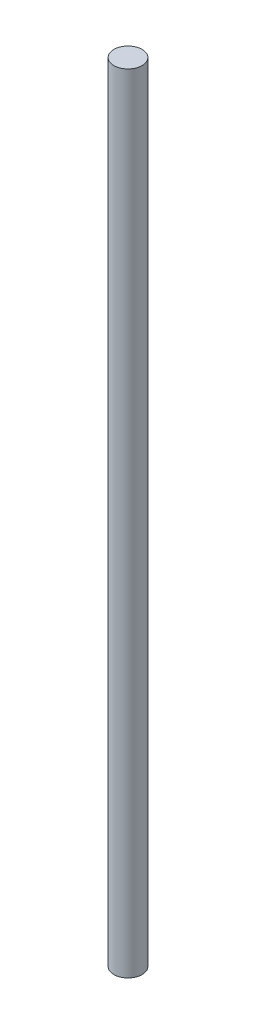
SolidWorks part; units mm, degrees
ref_plane "Front Plane" through (0, 0, 0) normal (0, 0, 1) x (1, 0, 0)
ref_plane "Top Plane" through (0, 0, 0) normal (0, 1, 0) x (1, 0, 0)
ref_plane "Right Plane" through (0, 0, 0) normal (1, 0, 0) x (0, 0, -1)
sketch "Sketch1" plane through (0, 0, 0) normal (0, 1, 0) x (1, 0, 0)
  circle A0 centre (0, 0) radius 2.5
  dimension "D1" = 5
extrude "Boss-Extrude1" add sketch "Sketch1" along normal blind 140
